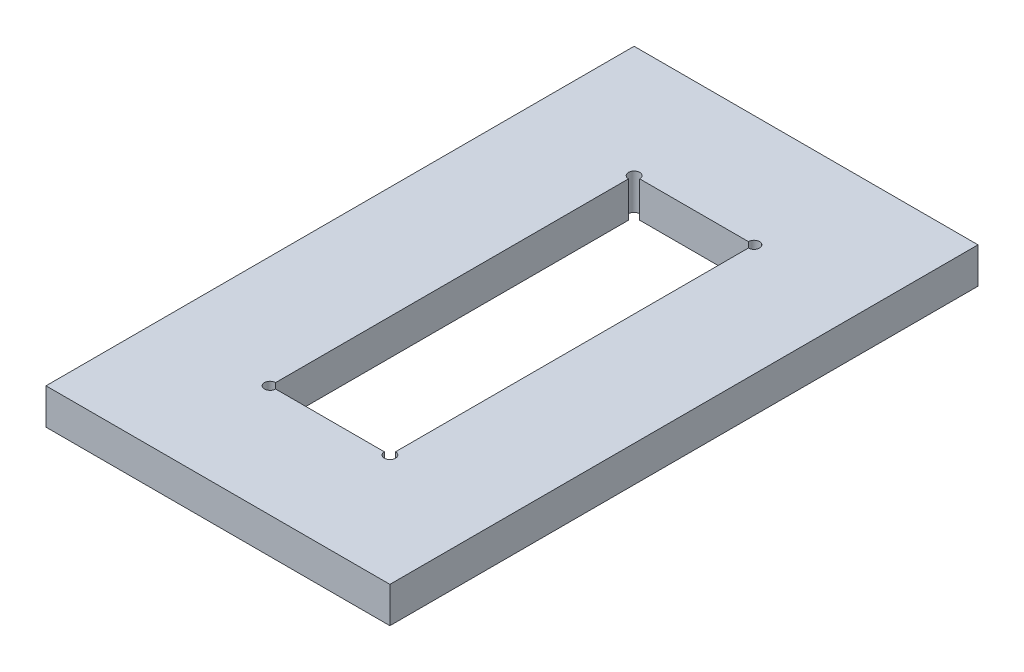
SolidWorks part; units mm, degrees
ref_plane "Front Plane" through (0, 0, 0) normal (0, 0, 1) x (1, 0, 0)
ref_plane "Top Plane" through (0, 0, 0) normal (0, 1, 0) x (1, 0, 0)
ref_plane "Right Plane" through (0, 0, 0) normal (1, 0, 0) x (0, 0, -1)
sketch "Sketch1" plane through (0, 0, 0) normal (0, 1, 0) x (1, 0, 0)
  line L0 (-10, -10) -> (-10, 42.5)
  line L1 (0.5, 0) -> (10.2, 0)
  line L2 (0, 0.5) -> (0, 32)
  line L3 (0.5, 32.5) -> (10.2, 32.5)
  line L4 (10.7, 0.5) -> (10.7, 32)
  line L5 (-10, 42.5) -> (20.7, 42.5)
  line L6 (20.7, -10) -> (20.7, 42.5)
  line L7 (-10, -10) -> (20.7, -10)
  line L9 (0, 0) -> (10.7, 0) construction
  line L10 (0, 0) -> (0, 32.5) construction
  line L11 (10.7, 0) -> (10.7, 32.5) construction
  line L12 (0, 32.5) -> (10.7, 32.5) construction
  arc A0 (0.5, 32.5) -> (0, 32) centre (0, 32.5) ccw
  arc A1 (10.7, 32) -> (10.2, 32.5) centre (10.7, 32.5) ccw
  arc A2 (0, 0.5) -> (0.5, 0) centre (0, 0) ccw
  arc A3 (10.2, 0) -> (10.7, 0.5) centre (10.7, 0) ccw
  dimension "D4" = 1
  dimension "D1" = 32.5
  dimension "D2" = 10.7
  dimension "D3" = 10
extrude "Boss-Extrude1" add sketch "Sketch1" along normal blind 3.2
